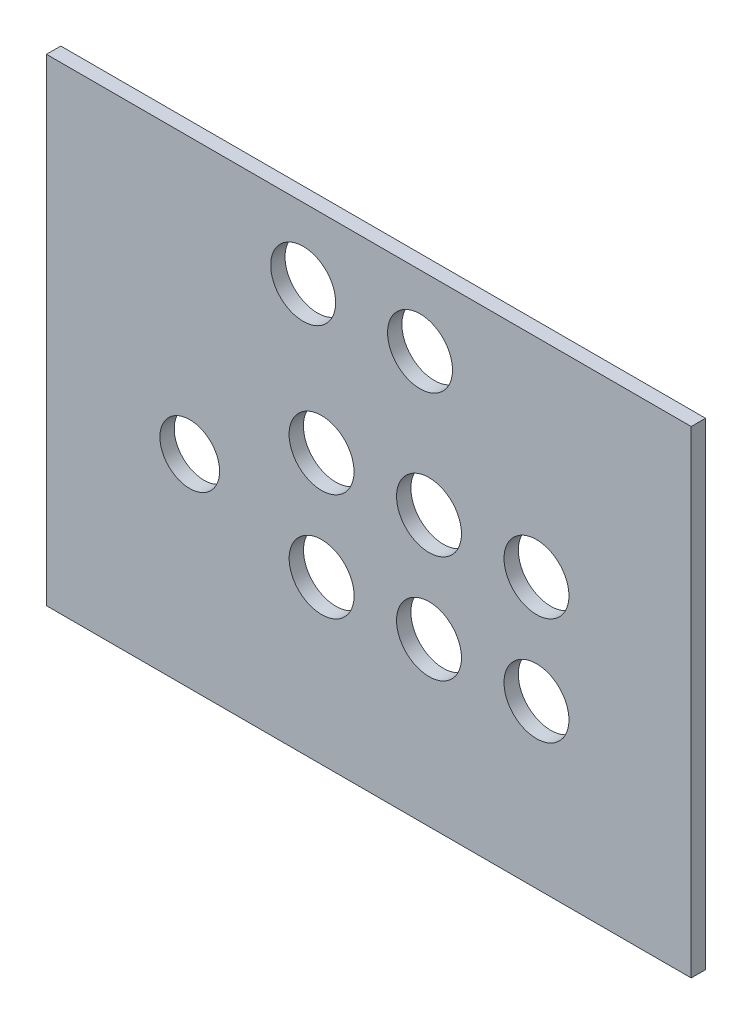
SolidWorks part; units mm, degrees
ref_plane "Plano frontal" through (0, 0, 0) normal (0, 0, 1) x (1, 0, 0)
ref_plane "Plano superior" through (0, 0, 0) normal (0, 1, 0) x (1, 0, 0)
ref_plane "Plano direito" through (0, 0, 0) normal (1, 0, 0) x (0, 0, -1)
sketch "Esboço1" plane through (0, 0, 0) normal (0, 0, 1) x (1, 0, 0)
  line L0 (0, 0) -> (0, 200)
  line L1 (0, 200) -> (-270, 200)
  line L2 (-270, 200) -> (-270, 0)
  line L3 (-270, 0) -> (0, 0)
  circle A0 centre (-210, 85) radius 12.5
  circle A1 centre (-154.8032, 113.0003) radius 13.6
  circle A2 centre (-109.8032, 112.9868) radius 13.6
  circle A3 centre (-64.8033, 113) radius 13.6
  circle A4 centre (-154.7745, 68.0003) radius 13.6
  circle A5 centre (-109.8032, 68.0003) radius 13.6
  circle A6 centre (-64.8033, 68.0003) radius 13.6
  circle A7 centre (-162.5, 170.4972) radius 13.6
  circle A8 centre (-113.572, 170.4972) radius 13.6
  point P11 (-109.4532, 152.2567)
  point P14 (-75.3259, 152.2567)
  point P17 (-147.1109, 119.3062)
  point P20 (-109.4532, 119.3062)
  point P23 (-75.3259, 119.3062)
  point P26 (-158.879, 170.4972)
  point P29 (-119.456, 170.4972)
  point P30 (0, 0)
  point P31 (0, 0)
  point P32 (0, 0)
  point P33 (-119.456, 170.4972)
  point P34 (0, 0)
  point P35 (-105.9228, 170.4972)
  point P36 (0, 0)
  point P37 (0, 0)
  point P38 (-113.572, 170.4972)
  point P39 (0, 0)
  point P40 (-113.572, 104.0078)
  point P41 (0, 0)
  point P42 (0, 0)
  point P43 (-102.3924, 71.0572)
  point P44 (-113.572, 71.0572)
  point P45 (0, 0)
  point P46 (-47.671, 104.0078)
  point P47 (-47.671, 104.0078)
  point P48 (-47.671, 71.0572)
  point P49 (-81.7983, 104.0078)
  point P50 (-47.671, 104.0078)
  point P51 (-32.3725, 26.9271)
  point P52 (-47.0826, 104.0078)
  point P53 (-47.0826, 71.0572)
  point P54 (-81.7983, 116.0572)
  point P55 (-47.0826, 116.0572)
  point P56 (-62.9694, 109.8918)
  point P57 (-94.754, 113)
  point P58 (-62.9694, 68.0003)
  point P59 (-28.2537, 68.0003)
  point P60 (-68.2537, 68.0003)
  point P61 (-28.2537, 68.0003)
  point P62 (0, 0)
  point P63 (0, 0)
  point P64 (0, 0)
  point P65 (-144.8031, 110.5384)
  point P66 (-144.7274, 68.0003)
  point P67 (-104.8032, 68.0003)
  point P68 (-64.8791, 68.0003)
  point P69 (-104.8032, 113.0003)
  point P70 (0, 0)
  point P71 (-64.8033, 68.0003)
  point P72 (-64.8033, 68.0003)
  point P73 (-109.8032, 68.0003)
  point P74 (-64.8033, 68.0003)
  point P75 (0, 0)
  dimension "D3" = 60
  dimension "D5" = 25
  dimension "D6" = 107.5
  dimension "D1" = 200
  dimension "D2" = 270
  dimension "D4" = 115
  dimension "D7" = 45
  dimension "D8" = 87
  dimension "D9" = 45
  dimension "D10" = 45
extrude "Ressalto-extrusão1" add sketch "Esboço1" along normal blind 6
